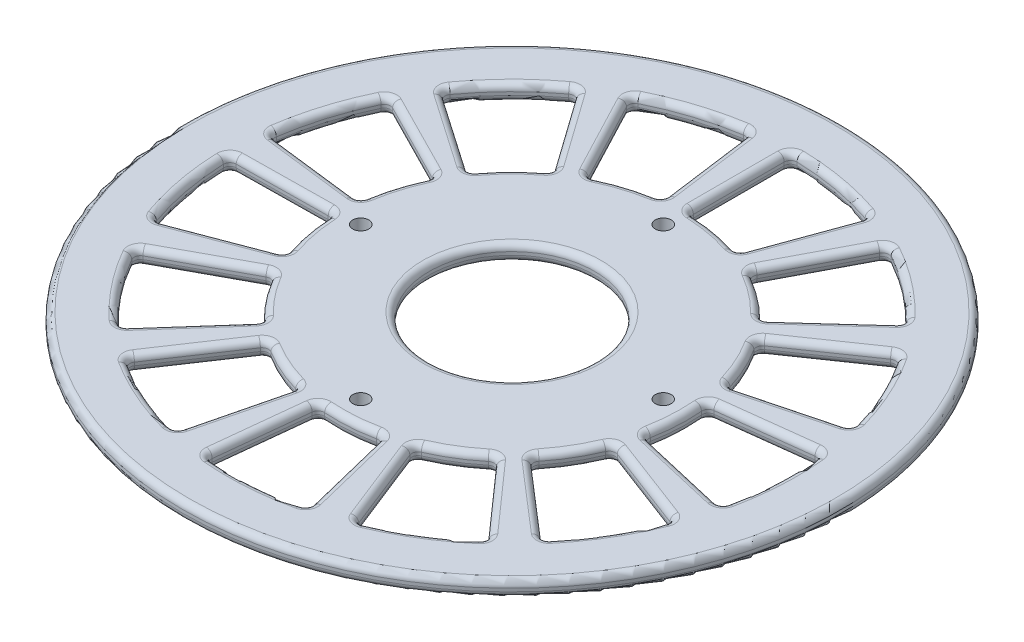
SolidWorks part; units mm, degrees
ref_plane "Front Plane" through (0, 0, 0) normal (0, 0, 1) x (1, 0, 0)
ref_plane "Top Plane" through (0, 0, 0) normal (0, 1, 0) x (1, 0, 0)
ref_plane "Right Plane" through (0, 0, 0) normal (1, 0, 0) x (0, 0, -1)
sketch "Sketch1" plane through (0, 0, 0) normal (0, 1, 0) x (1, 0, 0)
  line L0 (0, 0) -> (0, 26) construction
  line L1 (0, 0) -> (8.8925, 24.432) construction
  line L2 (0, 56.9649) -> (0, 85.4766)
  line L3 (19.4831, 53.5295) -> (29.2347, 80.3217)
  line L4 (26.4729, 50.4399) -> (39.723, 75.6858)
  line L5 (42.1279, 38.3437) -> (63.2134, 57.5353)
  line L6 (46.8812, 32.3598) -> (70.3459, 48.5562)
  line L7 (55.1216, 14.3739) -> (82.7107, 21.5682)
  line L8 (56.5496, 6.8664) -> (84.8534, 10.3031)
  line L9 (55.4876, -12.8888) -> (83.26, -19.3399)
  line L10 (53.2631, -20.2) -> (79.922, -30.3104)
  line L11 (43.1421, -37.1989) -> (64.7354, -55.8174)
  line L12 (37.7747, -42.6388) -> (56.6815, -63.9802)
  line L13 (20.9133, -52.9871) -> (31.3807, -79.5079)
  line L14 (13.6326, -55.3096) -> (20.4559, -82.9928)
  line L15 (-6.1066, -56.6366) -> (-9.163, -84.9841)
  line L16 (-13.6326, -55.3096) -> (-20.4559, -82.9928)
  line L17 (-31.7274, -47.3114) -> (-47.6075, -70.9914)
  line L18 (-37.7747, -42.6388) -> (-56.6815, -63.9802)
  line L19 (-50.08, -27.1477) -> (-75.1457, -40.7355)
  line L20 (-53.2631, -20.2) -> (-79.922, -30.3104)
  line L21 (-56.9598, -0.7648) -> (-85.4689, -1.1475)
  line L22 (-56.5496, 6.8664) -> (-84.8534, 10.3031)
  line L23 (-50.7908, 25.7934) -> (-76.2122, 38.7033)
  line L24 (-46.8812, 32.3598) -> (-70.3459, 48.5562)
  line L25 (-32.9862, 46.4425) -> (-49.4963, 69.6876)
  line L26 (-26.4729, 50.4399) -> (-39.723, 75.6858)
  line L27 (-7.6249, 56.4523) -> (-11.4413, 84.7074)
  circle A0 centre (0, 0) radius 103.5
  circle A1 centre (0, 0) radius 26
  arc A2 (27.9952, 82.9006) -> (2.0468, 87.4761) centre (0, 0) ccw
  arc A3 (16.9861, 52.3113) -> (1.9298, 54.9661) centre (0, 0) ccw
  arc A4 (2.0468, 87.4761) -> (0, 85.4766) centre (2, 85.4766) ccw
  arc A5 (27.9952, 82.9006) -> (29.2347, 80.3217) centre (27.3553, 81.0058) cw
  arc A6 (19.4831, 53.5295) -> (16.9861, 52.3113) centre (17.6038, 54.2135) cw
  arc A7 (1.9298, 54.9661) -> (0, 56.9649) centre (2, 56.9649) cw
  arc A8 (39.3507, 38.4255) -> (27.2528, 47.7733) centre (0, 0) ccw
  arc A9 (27.2528, 47.7733) -> (26.4729, 50.4399) centre (28.2438, 49.5105) cw
  arc A10 (63.3144, 60.3948) -> (42.4645, 76.505) centre (0, 0) ccw
  arc A11 (42.4645, 76.505) -> (39.723, 75.6858) centre (41.4939, 74.7563) ccw
  arc A12 (63.3144, 60.3948) -> (63.2134, 57.5353) centre (61.8672, 59.0144) cw
  arc A13 (42.1279, 38.3437) -> (39.3507, 38.4255) centre (40.7816, 39.8228) cw
  arc A14 (52.7006, 15.7369) -> (46.3325, 29.6361) centre (0, 0) ccw
  arc A15 (46.3325, 29.6361) -> (46.8812, 32.3598) centre (48.0173, 30.7138) cw
  arc A16 (84.129, 24.0533) -> (73.1541, 48.0076) centre (0, 0) ccw
  arc A17 (73.1541, 48.0076) -> (70.3459, 48.5562) centre (71.482, 46.9103) ccw
  arc A18 (84.129, 24.0533) -> (82.7107, 21.5682) centre (82.206, 23.5035) cw
  arc A19 (55.1216, 14.3739) -> (52.7006, 15.7369) centre (54.6169, 16.3092) cw
  arc A20 (53.9773, -10.5568) -> (54.798, 4.7097) centre (0, 0) ccw
  arc A21 (54.798, 4.7097) -> (56.5496, 6.8664) centre (56.7906, 4.8809) cw
  arc A22 (85.6707, -17.7985) -> (87.085, 8.5122) centre (0, 0) ccw
  arc A23 (87.085, 8.5122) -> (84.8534, 10.3031) centre (85.0945, 8.3176) ccw
  arc A24 (85.6707, -17.7985) -> (83.26, -19.3399) centre (83.7125, -17.3917) cw
  arc A25 (55.4876, -12.8888) -> (53.9773, -10.5568) centre (55.9402, -10.9407) cw
  arc A26 (42.8886, -34.4321) -> (50.7099, -21.2957) centre (0, 0) ccw
  arc A27 (50.7099, -21.2957) -> (53.2631, -20.2) centre (52.5539, -22.0701) cw
  arc A28 (67.5862, -55.573) -> (81.0657, -32.9332) centre (0, 0) ccw
  arc A29 (81.0657, -32.9332) -> (79.922, -30.3104) centre (79.2128, -32.1805) ccw
  arc A30 (67.5862, -55.573) -> (64.7354, -55.8174) centre (66.0414, -54.3027) cw
  arc A31 (43.1421, -37.1989) -> (42.8886, -34.4321) centre (44.4482, -35.6842) cw
  arc A32 (21.9745, -50.4194) -> (35.0048, -42.4225) centre (0, 0) ccw
  arc A33 (35.0048, -42.4225) -> (37.7747, -42.6388) centre (36.2777, -43.9651) cw
  arc A34 (34.0186, -80.6163) -> (56.4753, -66.834) centre (0, 0) ccw
  arc A35 (56.4753, -66.834) -> (56.6815, -63.9802) centre (55.1845, -65.3064) ccw
  arc A36 (34.0186, -80.6163) -> (31.3807, -79.5079) centre (33.241, -78.7736) cw
  arc A37 (20.9133, -52.9871) -> (21.9745, -50.4194) centre (22.7736, -52.2529) cw
  arc A38 (-3.9736, -54.8563) -> (11.2805, -53.8308) centre (0, 0) ccw
  arc A39 (11.2805, -53.8308) -> (13.6326, -55.3096) centre (11.6907, -55.7882) cw
  arc A40 (-7.3423, -87.1914) -> (18.9471, -85.424) centre (0, 0) ccw
  arc A41 (18.9471, -85.424) -> (20.4559, -82.9928) centre (18.514, -83.4714) ccw
  arc A42 (-7.3423, -87.1914) -> (-9.163, -84.9841) centre (-7.1745, -85.1985) cw
  arc A43 (-6.1066, -56.6366) -> (-3.9736, -54.8563) centre (-4.1181, -56.851) cw
  arc A44 (-29.0114, -46.7262) -> (-15.028, -52.9071) centre (0, 0) ccw
  arc A45 (-15.028, -52.9071) -> (-13.6326, -55.3096) centre (-15.5745, -54.831) cw
  arc A46 (-47.0212, -73.792) -> (-22.9217, -84.4443) centre (0, 0) ccw
  arc A47 (-22.9217, -84.4443) -> (-20.4559, -82.9928) centre (-22.3978, -82.5142) ccw
  arc A48 (-47.0212, -73.792) -> (-47.6075, -70.9914) centre (-45.9464, -72.1053) cw
  arc A49 (-31.7274, -47.3114) -> (-29.0114, -46.7262) centre (-30.0664, -48.4253) cw
  arc A50 (-47.4031, -27.8917) -> (-37.8938, -39.863) centre (0, 0) ccw
  arc A51 (-37.8938, -39.863) -> (-37.7747, -42.6388) centre (-39.2717, -41.3126) cw
  arc A52 (-75.928, -43.4878) -> (-59.5394, -64.1195) centre (0, 0) ccw
  arc A53 (-59.5394, -64.1195) -> (-56.6815, -63.9802) centre (-58.1785, -62.6539) ccw
  arc A54 (-75.928, -43.4878) -> (-75.1457, -40.7355) centre (-74.1925, -42.4938) cw
  arc A55 (-50.08, -27.1477) -> (-47.4031, -27.8917) centre (-49.1268, -28.906) cw
  arc A56 (-54.9353, -2.6676) -> (-52.0786, -17.6868) centre (0, 0) ccw
  arc A57 (-52.0786, -17.6868) -> (-53.2631, -20.2) centre (-53.9723, -18.33) cw
  arc A58 (-87.4407, -3.221) -> (-82.5173, -29.1057) centre (0, 0) ccw
  arc A59 (-82.5173, -29.1057) -> (-79.922, -30.3104) centre (-80.6312, -28.4404) ccw
  arc A60 (-87.4407, -3.221) -> (-85.4689, -1.1475) centre (-85.4421, -3.1474) cw
  arc A61 (-56.9598, -0.7648) -> (-54.9353, -2.6676) centre (-56.9329, -2.7646) cw
  arc A62 (-49.8825, 23.1677) -> (-54.3328, 8.5412) centre (0, 0) ccw
  arc A63 (-54.3328, 8.5412) -> (-56.5496, 6.8664) centre (-56.3085, 8.8518) cw
  arc A64 (-78.9218, 37.7837) -> (-86.5915, 12.5759) centre (0, 0) ccw
  arc A65 (-86.5915, 12.5759) -> (-84.8534, 10.3031) centre (-84.6123, 12.2885) ccw
  arc A66 (-78.9218, 37.7837) -> (-76.2122, 38.7033) centre (-77.1178, 36.9201) cw
  arc A67 (-50.7908, 25.7934) -> (-49.8825, 23.1677) centre (-51.6964, 24.0101) cw
  arc A68 (-33.4022, 43.6955) -> (-44.14, 32.8125) centre (0, 0) ccw
  arc A69 (-44.14, 32.8125) -> (-46.8812, 32.3598) centre (-45.7451, 34.0057) cw
  arc A70 (-52.3228, 70.1326) -> (-70.8287, 51.3765) centre (0, 0) ccw
  arc A71 (-70.8287, 51.3765) -> (-70.3459, 48.5562) centre (-69.2097, 50.2022) ccw
  arc A72 (-52.3228, 70.1326) -> (-49.4963, 69.6876) centre (-51.1268, 68.5295) cw
  arc A73 (-32.9862, 46.4425) -> (-33.4022, 43.6955) centre (-34.6168, 45.2844) cw
  arc A74 (-9.2698, 54.2132) -> (-23.8353, 49.5669) centre (0, 0) ccw
  arc A75 (-23.8353, 49.5669) -> (-26.4729, 50.4399) centre (-24.702, 51.3694) cw
  arc A76 (-13.7373, 86.4149) -> (-38.8398, 78.4074) centre (0, 0) ccw
  arc A77 (-38.8398, 78.4074) -> (-39.723, 75.6858) centre (-37.952, 76.6152) ccw
  arc A78 (-13.7373, 86.4149) -> (-11.4413, 84.7074) centre (-13.4233, 84.4397) cw
  arc A79 (-7.6249, 56.4523) -> (-9.2698, 54.2132) centre (-9.6069, 56.1846) cw
  point P165 (0, 0)
  dimension "D1" = 207
  dimension "D2" = 52
  dimension "D3" = 175
  dimension "D4" = 110
  dimension "D6" = 2
  dimension "D5" = 20
  dimension "D7" = 13
extrude "Boss-Extrude1" add sketch "Sketch1" along normal blind 5
fillet "Fillet1" radius 2 93 edges at (-16.7148, 5, -52.3986) (-50.8159, 5, -70.5052) (-62.2858, 5, -61.4551) (-58.6135, 5, -40.458) (-77.7606, 5, -38.8139) (-83.7109, 5, -25.4702) (-86.201, 5, -11.0735) (-70.7015, 5, -8.5847) (-71.2143, 5, 0.9562) (-86.8913, 5, 1.7691) (-85.9589, 5, 16.3497) (-81.4733, 5, 30.2545) (-76.1163, 5, 41.9469) (-47.2281, 5, 53.3095) (-22.2355, 5, 50.3049) (-30.4876, 5, 46.4702) (-39.6675, 5, 59.1514) (-17.0442, 5, 69.1512) (-8.7174, 5, 86.4711) (5.8693, 5, 87.3029) (20.2134, 5, 84.5261) (17.0442, 5, 69.1512) (36.4335, 5, 41.9712) (28.7689, 5, 46.8759) (20.9253, 5, 51.4889) (26.147, 5, 66.2475) (32.4662, 5, 80.6175) (57.1793, 5, 65.4505) (47.2281, 5, 53.3095) (51.7652, 5, 20.2321) (54.9207, 5, 2.9522) (70.7015, 5, -8.5847) (46.0567, 5, -31.1088) (53.6358, 5, -14.5664) (71.8655, 5, -48.8732) (58.6135, 5, -40.458) (26.3242, 5, -48.9491) (33.6281, 5, -43.5218) (40.7228, 5, -37.8237) (52.6706, 5, -47.9395) (40.9212, 5, -76.6726) (33.0979, 5, -63.0628) (9.5506, 5, -54.1644) (18.4807, 5, -52.416) (0.6024, 5, -86.9073) (0, 5, -71.2208) (0, 5, 26) (0, 5, 103.5) (-12.2298, 0, -86.0446) (-9.5331, 0, -70.5799) (-7.9951, 0, -55.0005) (-25.3304, 0, -49.4707) (-33.0979, 0, -63.0628) (-39.8544, 0, -77.2325) (-83.7109, 0, -25.4702) (-63.5015, 0, -32.2483) (-52.6183, 0, -16.0098) (-62.6128, 0, 33.9416) (-43.0664, 0, 34.2094) (-47.2281, 0, 53.3095) (-8.7174, 0, 86.4711) (-7.6348, 0, 70.8104) (20.2134, 0, 84.5261) (51.7652, 0, 20.2321) (83.9431, 0, -22.5122) (53.6358, 0, -14.5664) (50.0018, 0, -22.9089) (58.6135, 0, -40.458) (29.1579, 0, -81.8722) (9.5506, 0, -54.1644) (0.5612, 0, -55.5757) (0, 0, 103.5) (0, 0, 26) (53.4993, 0, -69.2392) (52.6706, 0, -47.9395) (33.6281, 0, -43.5218) (26.3242, 0, -48.9491) (87.3739, 0, 4.6967) (84.7898, 0, 19.0767) (54.9207, 0, 2.9522) (32.4662, 0, 80.6175) (28.7689, 0, 46.8759) (47.2281, 0, 53.3095) (57.1793, 0, 65.4505) (-35.3747, 0, 80.0305) (-47.904, 0, 72.5151) (-30.4876, 0, 46.4702) (-21.3832, 0, 84.2377) (-55.5632, 0, 1.3073) (-81.4733, 0, 30.2545) (-50.8159, 0, -70.5052) (-58.6135, 0, -40.458) (-71.1811, 0, -49.8647)
sketch "Sketch2" plane through (0, 0, 0) normal (0, -1, 0) x (1, 0, 0)
  circle A0 centre (0, 47.5) radius 2.5
  circle A1 centre (47.5, 0) radius 2.5
  circle A2 centre (0, -47.5) radius 2.5
  circle A3 centre (-47.5, 0) radius 2.5
  point P12 (0, 0)
  dimension "D1" = 5
  dimension "D2" = 47.5
  dimension "D3" = 4
extrude "Cut-Extrude1" cut sketch "Sketch2" against normal through all both and the other way through all
